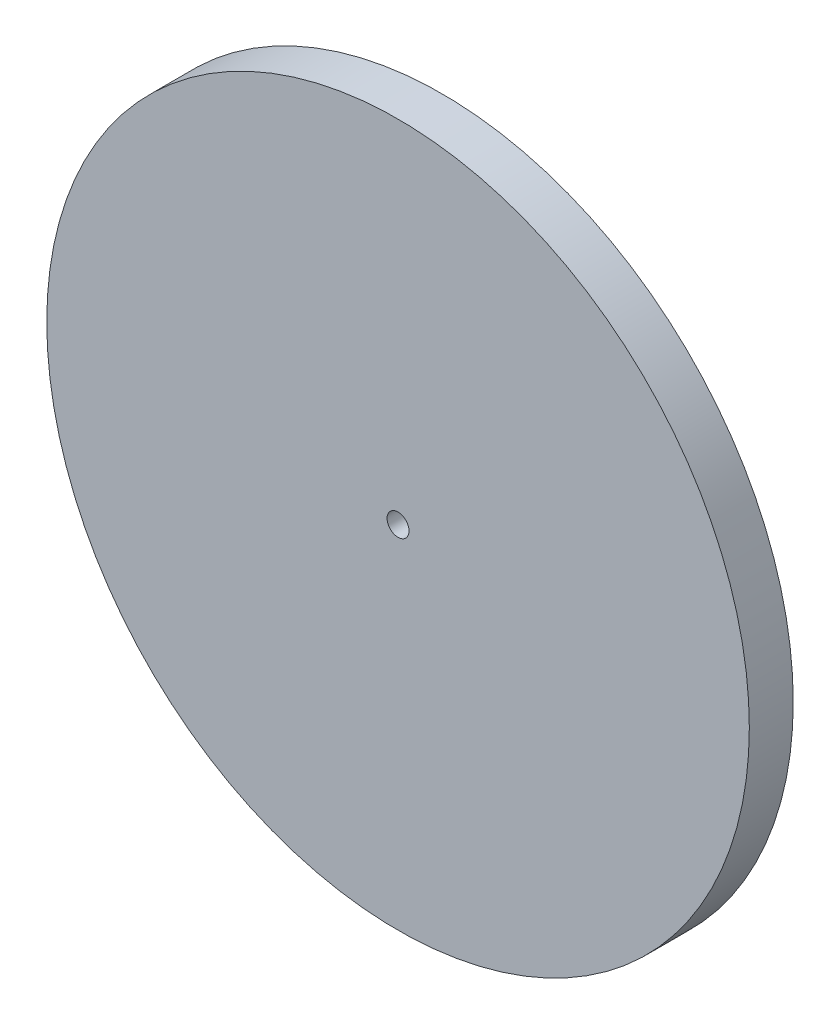
SolidWorks part; units mm, degrees
ref_plane "前视基准面" through (0, 0, 0) normal (0, 0, 1) x (1, 0, 0)
ref_plane "上视基准面" through (0, 0, 0) normal (0, 1, 0) x (1, 0, 0)
ref_plane "右视基准面" through (0, 0, 0) normal (1, 0, 0) x (0, 0, -1)
sketch "草图1" plane through (0, 0, 0) normal (0, 0, 1) x (1, 0, 0)
  circle A0 centre (0, 0) radius 160
  dimension "D1" = 320
extrude "凸台-拉伸1" add sketch "草图1" along normal blind 10
sketch "草图3" plane through (0, 0, 0) normal (0, 0, -1) x (-1, 0, 0)
  circle A1 centre (0, 0) radius 160
  circle A2 centre (0, 0) radius 160
  dimension "D1" = 0
extrude "拉伸-薄壁1" add sketch "草图3" along normal blind 10 thin thin type one direction reverse wall 5
sketch "草图4" plane through (0, 0, 10) normal (0, 0, 1) x (1, 0, 0)
  circle A0 centre (0, 0) radius 5
  dimension "D1" = 10
extrude "切除-拉伸1" cut sketch "草图4" against normal through all
